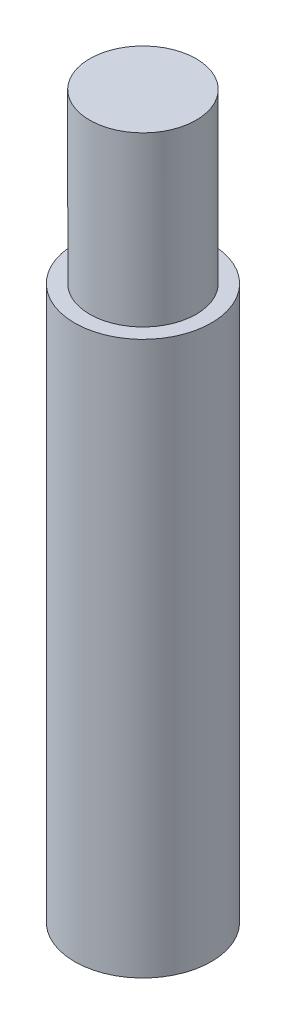
SolidWorks part; units mm, degrees
ref_plane "Alzado" through (0, 0, 0) normal (0, 0, 1) x (1, 0, 0)
ref_plane "Planta" through (0, 0, 0) normal (0, 1, 0) x (1, 0, 0)
ref_plane "Vista lateral" through (0, 0, 0) normal (1, 0, 0) x (0, 0, -1)
sketch "Croquis2" plane through (0, 0, 0) normal (0, 1, 0) x (1, 0, 0)
  circle A0 centre (0, 0) radius 12.2
  dimension "D1" = 24.4
extrude "Saliente-Extruir1" add sketch "Croquis2" along normal blind 98.7
sketch "Croquis3" plane through (0, 98.7, 0) normal (0, 1, 0) x (1, 0, 0)
  circle A0 centre (0, 0) radius 9.5
  dimension "D1" = 19
extrude "Saliente-Extruir2" add sketch "Croquis3" along normal up to surface (30 mm away)
